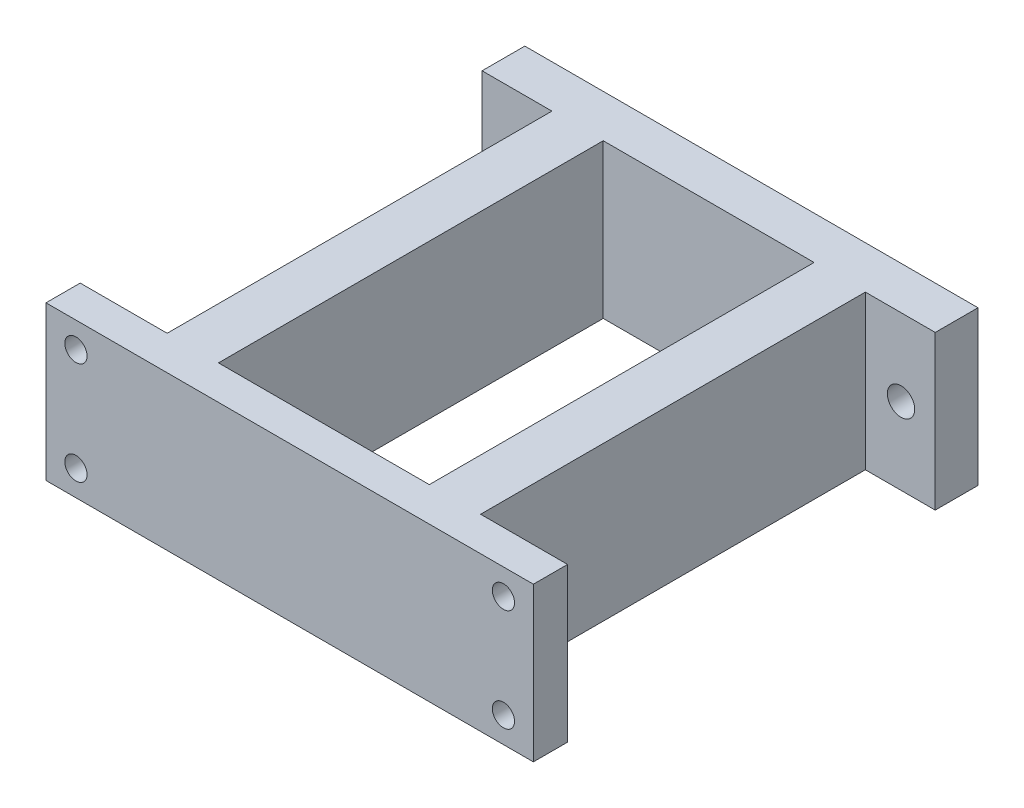
SolidWorks part; units mm, degrees
ref_plane "前视基准面" through (0, 0, 0) normal (0, 0, 1) x (1, 0, 0)
ref_plane "上视基准面" through (0, 0, 0) normal (0, 1, 0) x (1, 0, 0)
ref_plane "右视基准面" through (0, 0, 0) normal (1, 0, 0) x (0, 0, -1)
other "Configuration Table"
sketch "草图1" plane through (0, 0, 0) normal (0, 0, 1) x (1, 0, 0)
  line L0 (0, 0) -> (0, -50000) construction
  line L1 (-2.5, -9) -> (2.5, -9)
  line L2 (-2.5, -9) -> (-2.5, 9)
  line L3 (-2.5, 9) -> (2.5, 9)
  line L4 (2.5, -9) -> (2.5, 9)
  line L5 (-2.5, -9) -> (2.5, 9) construction
  line L6 (-2.5, 9) -> (2.5, -9) construction
  line L7 (0, 0) -> (50000, 0) construction
  line L8 (0, 0) -> (0, -6) construction
  circle A0 centre (0, -6) radius 1.3
  circle A1 centre (0, 6) radius 1.3
  point P0 (0, 0)
  dimension "D1" = 5
  dimension "D2" = 18
  dimension "D3" = 6
extrude "凸台-拉伸1" add sketch "草图1" along normal blind 4
sketch "草图2" plane through (0, 0, 4) normal (0, 0, 1) x (1, 0, 0)
  line L0 (-2.5, 9) -> (-2.5, -9)
  line L1 (-2.5, -9) -> (-7.5, -9)
  line L2 (-7.5, -9) -> (-7.5, 9)
  line L3 (-7.5, 9) -> (-2.5, 9)
  dimension "D1" = 18
  dimension "D2" = 5
extrude "凸台-拉伸2" add sketch "草图2" against normal blind 54
sketch "草图3" plane through (-7.5, 0, 0) normal (-1, 0, 0) x (0, 0, 1)
  line L0 (-50, 9) -> (-50, -9)
  line L1 (-50, -9) -> (-45, -9)
  line L2 (-50, -9) -> (4, -9) construction
  line L3 (-45, -9) -> (-45, 9)
  line L4 (-50, 9) -> (4, 9) construction
  line L5 (-45, 9) -> (-50, 9)
extrude "凸台-拉伸3" add sketch "草图3" along normal blind 53
sketch "草图4" plane through (0, 0, -50) normal (0, 0, -1) x (-1, 0, 0)
  line L0 (2.5, 9) -> (7.5, 9) construction
  line L1 (2.5, 9) -> (60.5, 9) construction
  line L2 (7.5, 9) -> (7.5, -9) construction
  line L3 (60.5, -9) -> (2.5, -9) construction
  line L4 (7.5, 0) -> (50007.5, 0) construction
  line L5 (60.5, 0) -> (7.5, 0) construction
  line L6 (60.5, 9) -> (60.5, -9) construction
  line L7 (7.5, 0) -> (34, 0) construction
  line L8 (34, 0) -> (34, 50000) construction
  line L9 (7.5, 0) -> (11.5, 0) construction
  line L10 (11.5, 0) -> (56.5, 0) construction
  circle A0 centre (11.5, 0) radius 1.6
  circle A1 centre (56.5, 0) radius 1.6
  point P10 (7.5, 0)
ref_plane "基准面1" through (-34, 0, 0) normal (-1, 0, 0) x (0, 1, 0)
mirror "镜向1" about plane through (-34, 0, 0) normal (-1, 0, 0) of "凸台-拉伸2"
mirror "镜向2" about plane through (-34, 0, 0) normal (-1, 0, 0) of "凸台-拉伸1"
extrude "切除-拉伸1" cut sketch "草图4" against normal blind 50
sketch "草图8" plane through (-7.5, 0, 0) normal (-1, 0, 0) x (0, 0, 1)
  line L0 (4, 9) -> (0, 9)
  line L1 (-45, 9) -> (4, 9) construction
  line L2 (0, 9) -> (0, -9)
  line L3 (-45, -9) -> (4, -9) construction
  line L4 (0, -9) -> (4, -9)
  line L5 (4, -9) -> (4, 9)
extrude "凸台-拉伸4" add sketch "草图8" along normal up to surface (53 mm away) up to face at (-60.5, 0, -20.5)
sketch "草图9" plane through (0, 0, 0) normal (0, 0, -1) x (-1, 0, 0)
  line L0 (7.5, 9) -> (7.5, -9)
  line L1 (7.5, -9) -> (60.5, -9)
  line L2 (60.5, -9) -> (60.5, 9)
  line L3 (60.5, 9) -> (7.5, 9)
  line L4 (34, 9) -> (34, -49991) construction
  line L5 (34, 9) -> (34, -49991) construction
  line L6 (59, 9) -> (59, 6) construction
  line L7 (34, 0) -> (59, 0) construction
  line L8 (59, 9) -> (59, -9) construction
  circle A0 centre (59, 6) radius 1.3
  circle A1 centre (59, -6) radius 1.3
  circle A2 centre (9, -6) radius 1.3
  circle A3 centre (9, 6) radius 1.3
  point P10 (34, 9)
  point P13 (34, -9)
  point P26 (0, 0)
  dimension "D1" = 12
extrude "切除-拉伸6" cut sketch "草图9" along direction (0, 0, 1) on the side against the normal blind 12 contours A3 | A2 | A0 | A1
sketch "草图14" plane through (2.5, 0, 0) normal (1, 0, 0) x (0, 0, -1)
  line L1 (-4, 9) -> (0, 9)
  line L2 (-4, 9) -> (-4, -9)
  line L3 (-4, -9) -> (0, -9)
  line L4 (0, 9) -> (0, -9)
extrude "切除-拉伸8" cut sketch "草图14" against normal blind 5
sketch "草图15" plane through (-70.5, 0, 0) normal (-1, 0, 0) x (0, 0, 1)
  line L0 (4, -9) -> (0, -9) construction
  line L1 (0, 9) -> (4, 9)
  line L2 (0, 9) -> (0, -9)
  line L3 (0, -9) -> (4, -9)
  line L4 (4, 9) -> (4, -9)
extrude "切除-拉伸9" cut sketch "草图15" against normal blind 5
sketch "草图16" plane through (0, 0, 0) normal (0, 0, -1) x (-1, 0, 0)
  line L0 (34, 9) -> (34, -49991) construction
  line L1 (60.5, 9) -> (7.5, 9) construction
  line L2 (60.5, -9) -> (7.5, -9) construction
  line L3 (34, 9) -> (15.6707, 9) construction
  line L4 (15.6707, 9) -> (15.6707, -9)
  line L5 (15.6707, -9) -> (21.6707, -9)
  line L6 (15.6707, 9) -> (21.6707, 9)
  line L7 (21.6707, 9) -> (21.6707, -9)
  line L8 (52.3293, 9) -> (46.3293, 9)
  line L9 (52.3293, 9) -> (52.3293, -9)
  line L10 (52.3293, -9) -> (46.3293, -9)
  line L11 (46.3293, 9) -> (46.3293, -9)
  point P4 (34, 9)
  point P7 (34, -9)
extrude "凸台-拉伸5" add sketch "草图16" along normal up to surface (45 mm away) up to face at (-13.1, 0, -45)
sketch "草图17" plane through (0, 0, 4) normal (0, 0, 1) x (1, 0, 0)
  line L0 (-2.5, 9) -> (-7.5, 9)
  line L1 (-2.5, 9) -> (-65.5, 9) construction
  line L2 (-7.5, 9) -> (-7.5, -9)
  line L3 (-65.5, -9) -> (-2.5, -9) construction
  line L4 (-7.5, -9) -> (-2.5, -9)
  line L5 (-2.5, -9) -> (-2.5, 9)
extrude "切除-拉伸10" cut sketch "草图17" against normal blind 77
sketch "草图19" plane through (-7.5, 0, 0) normal (1, 0, 0) x (0, 0, -1)
  line L0 (0, -9) -> (-4, -9) construction
  line L1 (-4, 9) -> (0, 9)
  line L2 (-4, 9) -> (-4, -9)
  line L3 (-4, -9) -> (0, -9)
  line L4 (0, 9) -> (0, -9)
  line L5 (0, 9) -> (0, -9) construction
extrude "凸台-拉伸6" add sketch "草图19" along normal blind 2
mirror "镜向3" about plane through (-34, 0, 0) normal (-1, 0, 0) of "凸台-拉伸5", "切除-拉伸10", "凸台-拉伸6"
